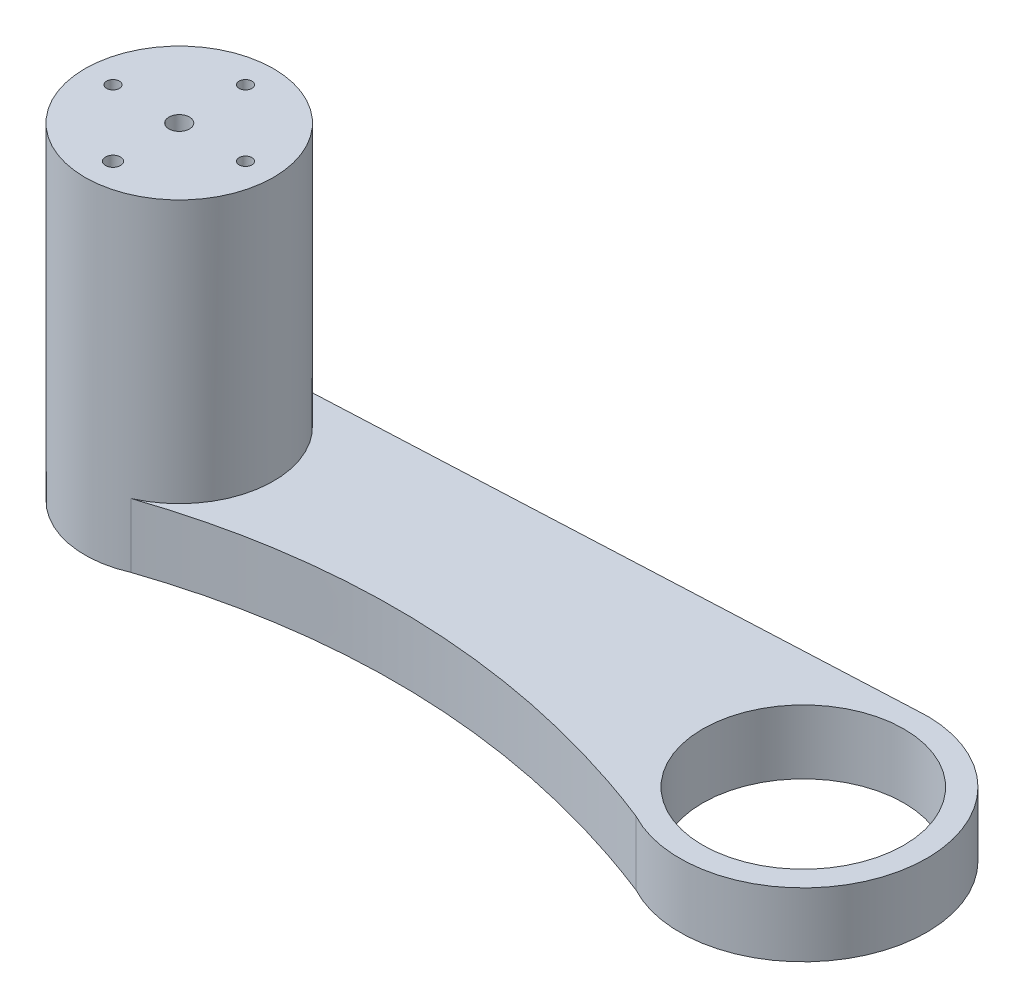
SolidWorks part; units mm, degrees
ref_plane "Płaszczyzna przednia" through (0, 0, 0) normal (0, 0, 1) x (1, 0, 0)
ref_plane "Płaszczyzna górna" through (0, 0, 0) normal (0, 1, 0) x (1, 0, 0)
ref_plane "Płaszczyzna prawa" through (0, 0, 0) normal (1, 0, 0) x (0, 0, -1)
sketch "Szkic1" plane through (0, 0, 0) normal (0, 1, 0) x (1, 0, 0)
  circle A0 centre (0, 0) radius 10.3
  circle A1 centre (0, 0) radius 1.125
  dimension "D1" = 20.6
  dimension "D2" = 2.25
extrude "Dodanie-wyciągnięcie1" add sketch "Szkic1" along normal blind 35.75 contours A0
hole_wizard "Otwory ustalające Ø2.5mm2" positions "Szkic4" profile "Szkic6" hole size "Ø2.5" standard "Ansi Metric" end condition through all
sketch "Szkic4" plane through (0, 0, 0) normal (0, -1, 0) x (1, 0, 0)
  point P0 (0, 0)
sketch "Szkic6" plane through (0, 0, 0) normal (1, 0, 0) x (0, 0, -1)
  line L0 (0, 0) -> (0, 35.75)
  line L1 (0, 35.75) -> (1.125, 35.75)
  line L2 (1.125, 35.75) -> (1.125, 0)
  line L5 (1.125, 0) -> (0, 0)
  line L11 (0, -6.35) -> (0, 107.95) construction
  dimension "Średnica otworu na wylot" = 2.25
  dimension "Głębokość otworu na wylot" = 35.75
sketch "Szkic7" plane through (0, 35.75, 0) normal (0, 1, 0) x (1, 0, 0)
  line L0 (0, 0) -> (10.1903, 0) construction
  line L1 (10.1903, 0) -> (68.2073, 0) construction
  line L2 (4.1699, -9.4182) -> (22.4618, -3.246) construction
  line L3 (22.4618, -3.246) -> (41.9342, -4.0772) construction
  line L4 (41.9342, -4.0772) -> (61.82, -11.8934) construction
  line L5 (66.9434, 13.4407) -> (0, 10.3)
  arc A0 (61.82, -11.8934) -> (66.9434, 13.4407) centre (68.2073, 0) ccw
  circle A1 centre (0, 0) radius 10.3 construction
  arc A2 (0, 10.3) -> (4.1699, -9.4182) centre (0, 0) cw
  spline S0 degree 3 poles (4.1699, -9.4182) (22.4618, -3.246) (41.9342, -4.0772) (61.82, -11.8934) knots 0 0 0 0 1 1 1 1
  dimension "D1" = 27
extrude "Dodanie-wyciągnięcie3" add sketch "Szkic7" against normal blind 7
hole_wizard "Otwory ustalające Ø2.5mm3" positions "Szkic10" profile "Szkic11" hole size "Ø2.5" standard "Ansi Metric" end condition through all
sketch "Szkic10" plane through (0, 35.75, 0) normal (0, 1, 0) x (1, 0, 0)
  point P0 (68.2073, 0)
sketch "Szkic11" plane through (68.2073, 35.75, 0) normal (1, 0, 0) x (0, 0, 1)
  line L0 (0, 0) -> (0, 35.75)
  line L1 (0, 35.75) -> (11, 35.75)
  line L2 (11, 35.75) -> (11, 0)
  line L5 (11, 0) -> (0, 0)
  line L11 (0, -6.35) -> (0, 107.95) construction
  dimension "Średnica otworu na wylot" = 22
  dimension "Głębokość otworu na wylot" = 35.75
mirror "Lustro1" about plane through (0, 0, 0) normal (0, 1, 0) of bodies 106
delete or keep bodies "Obiekt-Usuń/zachowaj 1" type delete bodies bodies 106
sketch "Szkic12" plane through (0, 0, 0) normal (0, 1, 0) x (1, 0, 0)
  circle A0 centre (0, 7.24) radius 0.7
  circle A1 centre (0, -7.24) radius 0.8203
  circle A2 centre (7.24, 0) radius 0.7
  circle A3 centre (-7.24, 0) radius 0.7
  dimension "D1" = 1.4
  dimension "D2" = 1.4
  dimension "D3" = 1.4
  dimension "D4" = 1.6407
  dimension "D5" = 7.24
  dimension "D6" = 7.24
  dimension "D7" = 7.24
  dimension "D8" = 7.24
extrude "Wytnij-wyciągnięcie1" cut sketch "Szkic12" against normal blind 7
